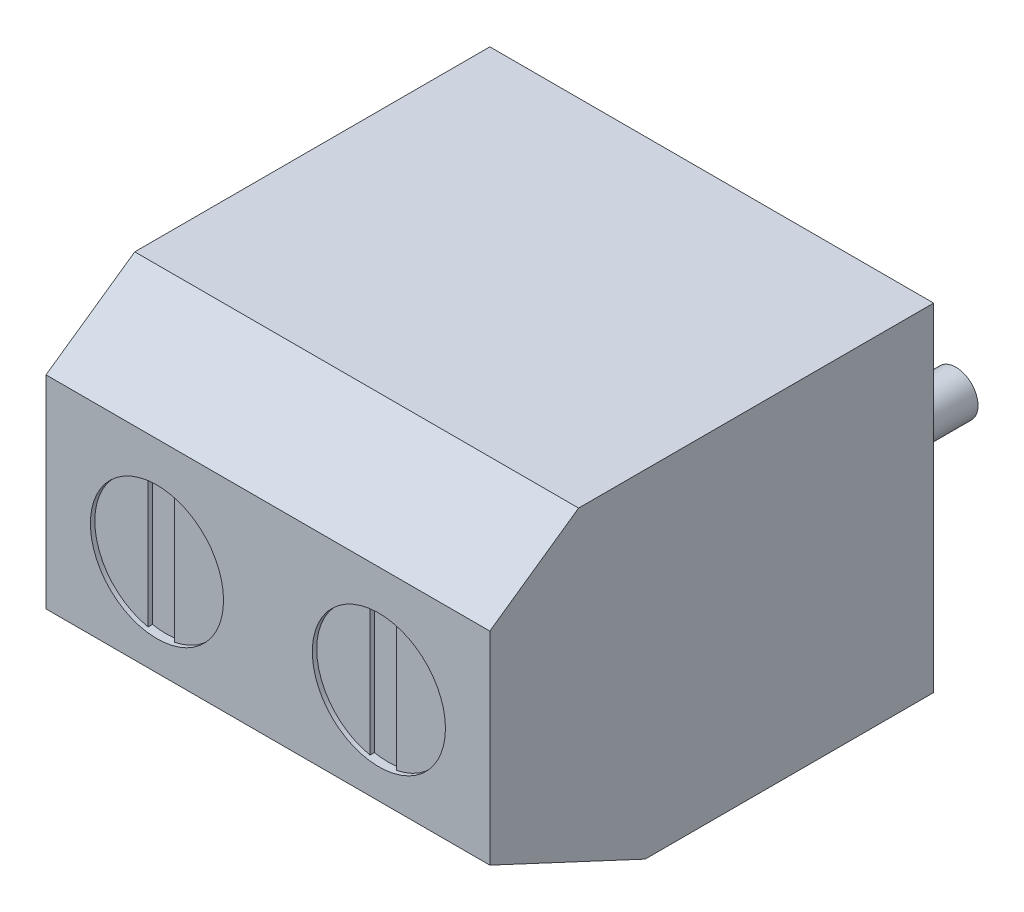
SolidWorks part; units mm, degrees
ref_plane "Спереди" through (0, 0, 0) normal (0, 0, 1) x (1, 0, 0)
ref_plane "Сверху" through (0, 0, 0) normal (0, 1, 0) x (1, 0, 0)
ref_plane "Справа" through (0, 0, 0) normal (1, 0, 0) x (0, 0, -1)
sketch "Эскиз1" plane through (0, 0, 0) normal (0, 0, 1) x (1, 0, 0)
  line L1 (-5, -3.8) -> (5, -3.8)
  line L2 (-5, -3.8) -> (-5, 3.8)
  line L3 (-5, 3.8) -> (5, 3.8)
  line L4 (5, -3.8) -> (5, 3.8)
  line L5 (-5, -3.8) -> (5, 3.8) construction
  line L6 (-5, 3.8) -> (5, -3.8) construction
  point P0 (0, 0)
  dimension "D1" = 10
  dimension "D2" = 7.6
extrude "Бобышка-Вытянуть1" add sketch "Эскиз1" along normal blind 10
sketch "Эскиз2" plane through (0, 0, 10) normal (0, 0, 1) x (1, 0, 0)
  line L0 (5, -3.8) -> (5, 3.8) construction
  circle A0 centre (2.5, 0) radius 1.5
  dimension "D2" = 3
  dimension "D1" = 2.5
extrude "Вырез-Вытянуть1" cut sketch "Эскиз2" against normal blind 0.1
sketch "Эскиз3" plane through (0, 0, 9.9) normal (0, 0, 1) x (1, 0, 0)
  line L0 (2.2, -1.4697) -> (2.2, 1.4697)
  line L1 (2.8, -1.4697) -> (2.8, 1.4697)
  line L2 (0, -4.18) -> (0, 4.18) construction
  arc A0 (2.2, 1.4697) -> (2.8, 1.4697) centre (2.5, 0) cw
  circle A1 centre (2.5, 0) radius 1.5 construction
  arc A2 (2.2, -1.4697) -> (2.8, -1.4697) centre (2.5, 0) ccw
  dimension "D1" = 0.6
extrude "Вырез-Вытянуть2" cut sketch "Эскиз3" against normal blind 0.1
sketch "Эскиз4" plane through (0, -3.8, 0) normal (0, -1, 0) x (1, 0, 0)
  line L0 (-5, 0) -> (5, 0) construction
  line L1 (1, 5.2) -> (4, 5.2)
  line L2 (1, 5.2) -> (1, 0.5)
  line L3 (1, 0.5) -> (4, 0.5)
  line L4 (4, 5.2) -> (4, 0.5)
  line L5 (1, 5.2) -> (4, 0.5) construction
  line L6 (1, 0.5) -> (4, 5.2) construction
  line L8 (5, 10) -> (5, 0) construction
  point P0 (2.5, 2.85)
  dimension "D1" = 0.5
  dimension "D2" = 3
  dimension "D3" = 2.5
  dimension "D4" = 4.7
extrude "Вырез-Вытянуть3" cut sketch "Эскиз4" against normal blind 2
sketch "Эскиз5" plane through (0, 0, 0) normal (0, 0, -1) x (-1, 0, 0)
  line L0 (-5, -3.8) -> (-5, 3.8) construction
  line L1 (-5, 3.8) -> (5, 3.8) construction
  circle A0 centre (-2.5, -0.7) radius 0.5
  point P4 (0, 0)
  dimension "D2" = 1
  dimension "D1" = 2.5
  dimension "D3" = 4.5
extrude "Бобышка-Вытянуть2" add sketch "Эскиз5" along normal blind 3
pattern_linear "Линейный массив1" count 2 spacing 5 along (-1, 0, 0) of "Вырез-Вытянуть1", "Вырез-Вытянуть2", "Вырез-Вытянуть3", "Бобышка-Вытянуть2"
chamfer "Фаска1" distance 3.5 angle 25 1 edges at (0, -3.8, 10)
chamfer "Фаска2" distance 2 angle 35 1 edges at (0, 3.8, 10)
equation "\"N\"= 2"
equation "\"D1@Эскиз1\"=\"N\"*5"
equation "\"D1@Линейный массив1\"=\"N\""
